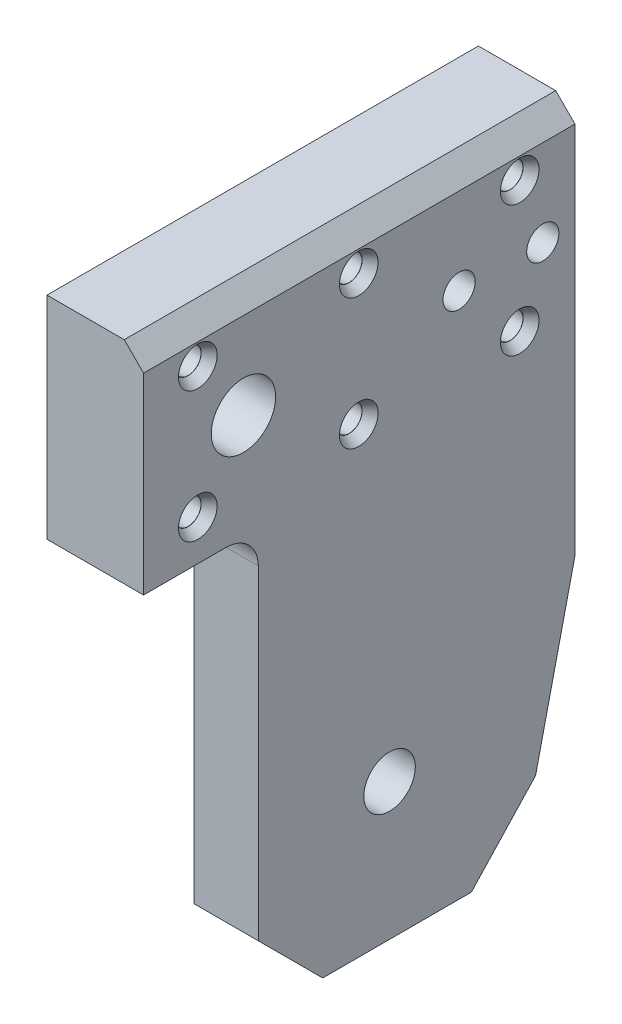
SolidWorks part; units mm, degrees
ref_plane "Спереди" through (0, 0, 0) normal (0, 0, 1) x (1, 0, 0)
ref_plane "Сверху" through (0, 0, 0) normal (0, 1, 0) x (1, 0, 0)
ref_plane "Справа" through (0, 0, 0) normal (1, 0, 0) x (0, 0, -1)
sketch "Эскиз1" plane through (0, 0, 0) normal (1, 0, 0) x (0, 0, -1)
  line L0 (-24.5825, -0.0006) -> (-24.5825, -32.8457)
  line L1 (-24.5825, -0.0006) -> (42.4175, -0.0006)
  line L2 (-6.7663, -32.8457) -> (-6.7663, -98.2589)
  line L3 (-6.7663, -98.2589) -> (33.8276, -98.2589)
  line L4 (42.4175, -0.0006) -> (42.4175, -61.0273)
  line L5 (-24.5825, -32.8457) -> (-6.7663, -32.8457)
  line L6 (33.8276, -98.2589) -> (42.4175, -61.0273)
  circle A2 centre (13.6201, -77.0297) radius 4
extrude "Вытянуть1" add sketch "Эскиз1" along normal blind 15
sketch "Эскиз4" plane through (0, 0, 0) normal (-1, 0, 0) x (0, 0, 1)
  line L0 (-42.4175, -40.2022) -> (16.8145, -40.2022)
  line L1 (16.8145, -40.2022) -> (16.8145, -112.0276)
  line L2 (16.8145, -112.0276) -> (-42.4175, -112.0276)
  line L3 (-42.4175, -40.2022) -> (-42.4175, -112.0276)
extrude "Вытянуть3" cut sketch "Эскиз4" against normal blind 5
sketch "Эскиз5" plane through (15, 0, 0) normal (1, 0, 0) x (0, 0, -1)
  circle A0 centre (-9.0688, -16.4232) radius 5
  circle A1 centre (24.4175, -16.4232) radius 2.5
  circle A2 centre (37.4175, -16.4232) radius 2.5
extrude "Вырез-Вытянуть1" cut sketch "Эскиз5" against normal through all
chamfer "Фаска1" distance 10 angle 45 1 edges at (10, -98.2589, 6.7663)
chamfer "Фаска2" distance 7.5 angle 47 1 edges at (10, -98.2589, -33.8276)
fillet "Скругление1" radius 5 1 edges at (7.5, -32.8457, 6.7663)
sketch "Эскиз6" plane through (15, 0, 0) normal (1, 0, 0) x (0, 0, -1)
  circle A0 centre (-16.1641, -6.2765) radius 2
  circle A1 centre (8.8359, -6.2765) radius 2
  circle A2 centre (33.8359, -6.2765) radius 2
  circle A3 centre (-16.1641, -26.5698) radius 2
  circle A4 centre (8.8359, -26.5698) radius 2
  circle A5 centre (33.8359, -26.5698) radius 2
extrude "Вырез-Вытянуть2" cut sketch "Эскиз6" against normal through all
sketch "Эскиз7" plane through (15, 0, 0) normal (1, 0, 0) x (0, 0, -1)
  circle A0 centre (-16.1641, -6.2765) radius 3
  circle A1 centre (8.8359, -6.2765) radius 3
  circle A2 centre (33.8359, -6.2765) radius 3
  circle A3 centre (-16.1641, -26.5698) radius 3
  circle A4 centre (8.8359, -26.5698) radius 3
  circle A5 centre (33.8359, -26.5698) radius 3
extrude "Вырез-Вытянуть3" cut sketch "Эскиз7" against normal blind 1.5 draft 33
chamfer "Фаска3" distance 3 angle 45 1 edges at (15, -0.0006, -8.9175)
